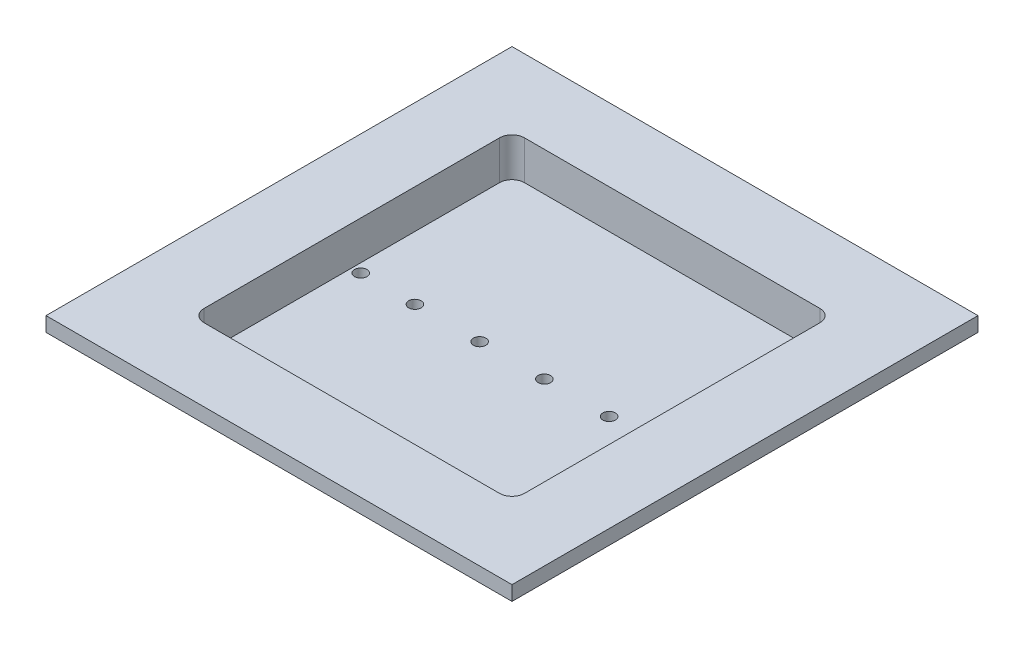
SolidWorks part; units mm, degrees
ref_plane "Front Plane" through (0, 0, 0) normal (0, 0, 1) x (1, 0, 0)
ref_plane "Top Plane" through (0, 0, 0) normal (0, 1, 0) x (1, 0, 0)
ref_plane "Right Plane" through (0, 0, 0) normal (1, 0, 0) x (0, 0, -1)
sketch "Sketch1" plane through (0, 0, 0) normal (0, 1, 0) x (1, 0, 0)
  line L1 (74.8, 74.8) -> (0, 74.8)
  line L2 (74.8, 74.8) -> (74.8, 0)
  line L3 (74.8, 0) -> (0, 0)
  line L4 (0, 74.8) -> (0, 0)
  line L5 (74.8, 74.8) -> (0, 0) construction
  line L6 (74.8, 0) -> (0, 74.8) construction
  dimension "D1" = 74.8
  dimension "D2" = 74.8
extrude "Boss-Extrude1" add sketch "Sketch1" along normal blind 2.3375
sketch "Sketch2" plane through (0, 0, 0) normal (0, 1, 0) x (1, 0, 0)
  line L1 (74.8, 0) -> (74.8, 74.8) construction
  line L2 (65.45, 65.45) -> (9.35, 65.45)
  line L3 (65.45, 65.45) -> (65.45, 9.35)
  line L4 (65.45, 9.35) -> (9.35, 9.35)
  line L5 (9.35, 65.45) -> (9.35, 9.35)
  line L6 (65.45, 65.45) -> (9.35, 9.35) construction
  line L7 (65.45, 9.35) -> (9.35, 65.45) construction
  line L8 (74.8, 74.8) -> (0, 74.8) construction
  point P2 (37.4, 37.4)
  dimension "D1" = 56.1
  dimension "D2" = 56.1
  dimension "D3" = 9.35
  dimension "D4" = 9.35
extrude "Boss-Extrude2" add sketch "Sketch2" against normal blind 7.5
chamfer "Chamfer1" distance 0.25 angle 45 8 edges at (37.4, 0, -65.45) (9.35, 0, -37.4) (65.45, 0, -37.4) (37.4, 0, -9.35) (37.4, -7.5, -9.35) (65.45, -7.5, -37.4) (37.4, -7.5, -65.45) (9.35, -7.5, -37.4)
sketch "Sketch3" plane through (0, 2.3375, 0) normal (0, 1, 0) x (1, 0, 0)
  line L1 (61.1125, 63.1125) -> (13.6875, 63.1125)
  line L2 (63.1125, 61.1125) -> (63.1125, 13.6875)
  line L3 (61.1125, 11.6875) -> (13.6875, 11.6875)
  line L4 (11.6875, 61.1125) -> (11.6875, 13.6875)
  line L5 (63.1125, 63.1125) -> (11.6875, 11.6875) construction
  line L6 (63.1125, 11.6875) -> (11.6875, 63.1125) construction
  line L8 (0, 0) -> (74.8, 0) construction
  line L9 (0, 74.8) -> (0, 0) construction
  arc A0 (63.1125, 13.6875) -> (61.1125, 11.6875) centre (61.1125, 13.6875) cw
  arc A1 (11.6875, 13.6875) -> (13.6875, 11.6875) centre (13.6875, 13.6875) ccw
  arc A2 (11.6875, 61.1125) -> (13.6875, 63.1125) centre (13.6875, 61.1125) cw
  arc A3 (63.1125, 61.1125) -> (61.1125, 63.1125) centre (61.1125, 61.1125) ccw
  point P0 (37.4, 37.4)
  dimension "D5" = 2
  dimension "D1" = 51.425
  dimension "D2" = 51.425
  dimension "D3" = 37.4
  dimension "D4" = 37.4
extrude "Cut-Extrude1" cut sketch "Sketch3" against normal blind 6.2333
sketch "Sketch4" plane through (0, -3.8958, 0) normal (0, 1, 0) x (1, 0, 0)
  line L0 (63.1125, 63.1175) -> (11.6825, 63.1175)
  line L1 (63.1125, 63.1175) -> (63.1125, 11.6875)
  line L2 (63.1125, 11.6875) -> (11.6825, 11.6875)
  line L3 (11.6825, 63.1175) -> (11.6825, 11.6875)
  line L4 (14.5419, 63.1175) -> (14.5419, 11.6875)
  line L5 (60.2531, 63.1175) -> (60.2531, 11.6875)
  line L6 (56.0975, 63.1125) -> (56.0975, 11.6875)
  line L7 (49.8642, 11.6875) -> (49.8642, 63.1125)
  line L8 (45.7086, 63.1125) -> (45.7086, 11.6875)
  line L9 (39.4753, 63.1125) -> (39.4753, 11.6875)
  line L10 (37.3975, 63.1175) -> (37.3975, 11.6875) construction
  line L11 (13.6875, 11.6875) -> (61.1125, 11.6875) construction
  line L12 (63.1125, 13.6875) -> (63.1125, 61.1125) construction
  line L13 (61.1125, 63.1125) -> (13.6875, 63.1125) construction
  line L14 (61.1125, 63.1125) -> (13.6875, 63.1125) construction
  line L15 (13.6875, 11.6875) -> (61.1125, 11.6875) construction
  circle A0 centre (52.9825, 37.4025) radius 1
  circle A1 centre (42.5886, 37.4075) radius 1
  circle A2 centre (32.1986, 37.4075) radius 1
  circle A3 centre (21.8086, 37.4075) radius 1
  circle A4 centre (13.1125, 37.4075) radius 1
  circle A5 centre (61.6825, 37.4075) radius 1
  point P32 (34.3448, 33.4807)
  point P35 (60.2531, 63.1175)
  point P36 (56.0975, 63.1125)
  point P39 (49.8642, 63.1125)
  point P42 (45.7086, 63.1125)
  point P43 (39.4753, 63.1125)
  point P44 (45.7086, 11.6875)
  point P47 (49.8642, 11.6875)
  point P48 (56.0975, 11.6875)
  point P49 (60.2531, 11.6875)
  point P50 (39.4753, 11.6875)
  dimension "D3" = 2
  dimension "D5" = 2
  dimension "D7" = 2
  dimension "D23" = 2
  dimension "D24" = 2
  dimension "D1" = 3.115
  dimension "D2" = 25.715
  dimension "D4" = 25.72
  dimension "D6" = 3.12
  dimension "D8" = 1.43
  dimension "D9" = 51.43
  dimension "D10" = 51.43
  dimension "D11" = 2.8594
  dimension "D12" = 8.6961
  dimension "D13" = 10.39
  dimension "D14" = 10.39
  dimension "D15" = 6.2333
  dimension "D16" = 4.1556
  dimension "D17" = 6.2333
  dimension "D18" = 4.1556
  dimension "D19" = 2.8594
  dimension "D20" = 51.43
  dimension "D21" = 25.72
  dimension "D22" = 25.72
extrude "Cut-Extrude2" cut sketch "Sketch4" against normal blind 4 contours A4 | A3 | A2 | A1 | A0 | A5
